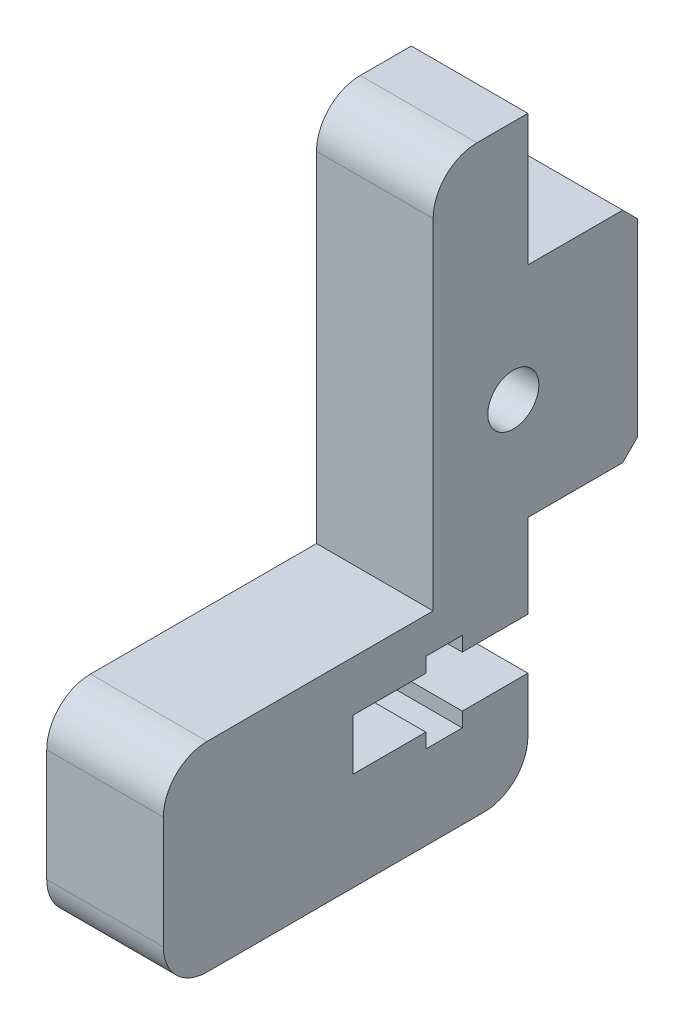
SolidWorks part; units mm, degrees
ref_plane "Front Plane" through (0, 0, 0) normal (0, 0, 1) x (1, 0, 0)
ref_plane "Top Plane" through (0, 0, 0) normal (0, 1, 0) x (1, 0, 0)
ref_plane "Right Plane" through (0, 0, 0) normal (1, 0, 0) x (0, 0, -1)
sketch "Sketch1" plane through (0, 0, 0) normal (1, 0, 0) x (0, 0, -1)
  line L0 (28.0829, 19.0972) -> (34.5829, 19.0972)
  line L1 (34.5829, 19.0972) -> (35.5829, 20.0972)
  line L2 (35.5829, 20.0972) -> (35.5829, 33.0972)
  line L3 (35.5829, 33.0972) -> (34.5829, 34.0972)
  line L4 (34.5829, 34.0972) -> (28.0829, 34.0972)
  line L5 (28.0829, 34.0972) -> (28.0829, 43.0972)
  line L6 (28.0829, 43.0972) -> (24.5829, 43.0972)
  line L7 (21.5829, 40.0972) -> (21.5829, 16.7972)
  line L8 (21.5829, 16.7972) -> (6.0829, 16.7972)
  line L9 (3.0829, 13.7972) -> (3.0829, 6.0972)
  line L10 (6.0829, 3.0972) -> (25.0829, 3.0972)
  line L11 (28.0829, 6.0972) -> (28.0829, 9.8472)
  line L12 (28.0829, 9.8472) -> (23.5829, 9.8472)
  line L13 (23.5829, 9.8472) -> (23.5829, 8.8472)
  line L14 (23.5829, 8.8472) -> (21.0829, 8.8472)
  line L15 (21.0829, 8.8472) -> (21.0829, 9.8472)
  line L16 (21.0829, 9.8472) -> (16.0829, 9.8472)
  line L17 (16.0829, 9.8472) -> (16.0829, 13.3472)
  line L18 (16.0829, 13.3472) -> (21.0829, 13.3472)
  line L19 (21.0829, 13.3472) -> (21.0829, 14.3472)
  line L20 (21.0829, 14.3472) -> (23.5829, 14.3472)
  line L21 (23.5829, 14.3472) -> (23.5829, 13.3472)
  line L22 (23.5829, 13.3472) -> (28.0829, 13.3472)
  line L23 (28.0829, 13.3472) -> (28.0829, 19.0972)
  circle A0 centre (27.0829, 26.5972) radius 1.75
  arc A1 (24.5829, 43.0972) -> (21.5829, 40.0972) centre (24.5829, 40.0972) ccw
  arc A2 (6.0829, 16.7972) -> (3.0829, 13.7972) centre (6.0829, 13.7972) ccw
  arc A3 (3.0829, 6.0972) -> (6.0829, 3.0972) centre (6.0829, 6.0972) ccw
  arc A4 (25.0829, 3.0972) -> (28.0829, 6.0972) centre (25.0829, 6.0972) ccw
extrude "Extrude1" add sketch "Sketch1" along normal blind 8
sketch "Sketch2" plane through (0, 0, -16.0829) normal (0, 0, -1) x (-1, 0, 0)
  line L0 (0, 13.3472) -> (-8, 9.8472)
  circle A0 centre (-4, 11.5972) radius 1
  dimension "D1" = 2
extrude "Extrude2" cut sketch "Sketch2" against normal blind 1 contours A0
